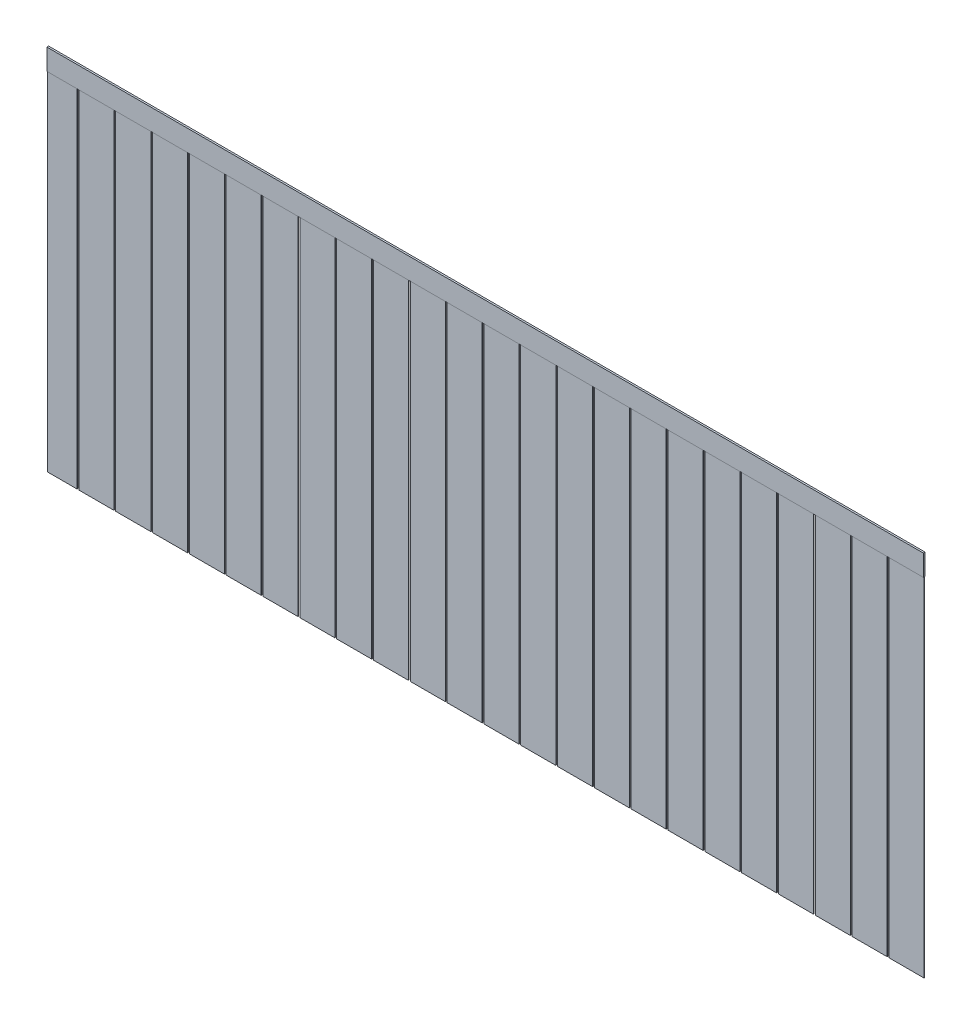
SolidWorks part; units mm, degrees
ref_plane "Alzado" through (0, 0, 0) normal (0, 0, 1) x (1, 0, 0)
ref_plane "Planta" through (0, 0, 0) normal (0, 1, 0) x (1, 0, 0)
ref_plane "Vista lateral" through (0, 0, 0) normal (1, 0, 0) x (0, 0, -1)
sketch "Croquis1" plane through (0, 0, 0) normal (0, 0, 1) x (1, 0, 0)
  line L1 (0, 0) -> (5000, 0)
  line L2 (0, 0) -> (0, -2100)
  line L3 (0, -2100) -> (5000, -2100)
  line L4 (5000, 0) -> (5000, -2100)
  dimension "D1" = 5000
  dimension "D2" = 2100
extrude "Saliente-Extruir1" add sketch "Croquis1" along normal blind 10
sketch "Croquis2" plane through (0, 0, 10) normal (0, 0, 1) x (1, 0, 0)
  line L0 (5000, -2100) -> (5000, 0) construction
  line L1 (0, -2100) -> (5000, -2100)
  line L2 (0, -2100) -> (0, -120)
  line L3 (0, -120) -> (5000, -120)
  line L4 (5000, -2100) -> (5000, -120)
  line L5 (5000, 0) -> (0, 0) construction
  dimension "D1" = 120
extrude "Cortar-Extruir1" cut sketch "Croquis2" against normal blind 3
sketch "Croquis3" plane through (0, 0, 0) normal (0, 0, -1) x (-1, 0, 0)
  line L1 (-5000, -2100) -> (0, -2100)
  line L2 (-5000, -2100) -> (-5000, -120)
  line L3 (-5000, -120) -> (0, -120)
  line L4 (0, -2100) -> (0, -120)
extrude "Cortar-Extruir2" cut sketch "Croquis3" against normal blind 3
sketch "Croquis4" plane through (0, 0, 3) normal (0, 0, -1) x (-1, 0, 0)
  line L0 (-5000, -2100) -> (0, -2100) construction
  line L1 (-4800, -2100) -> (-4790, -2100)
  line L2 (-4800, -2100) -> (-4800, -120)
  line L3 (-4800, -120) -> (-4790, -120)
  line L4 (-4790, -2100) -> (-4790, -120)
  line L5 (0, -120) -> (-5000, -120) construction
  line L6 (-5000, -120) -> (-5000, -2100) construction
  dimension "D1" = 200
  dimension "D2" = 10
extrude "Cortar-Extruir3" cut sketch "Croquis4" against normal blind 8
pattern_linear "MatrizL1" count 23 spacing 210 along (-1, 0, 0) of "Cortar-Extruir3"
